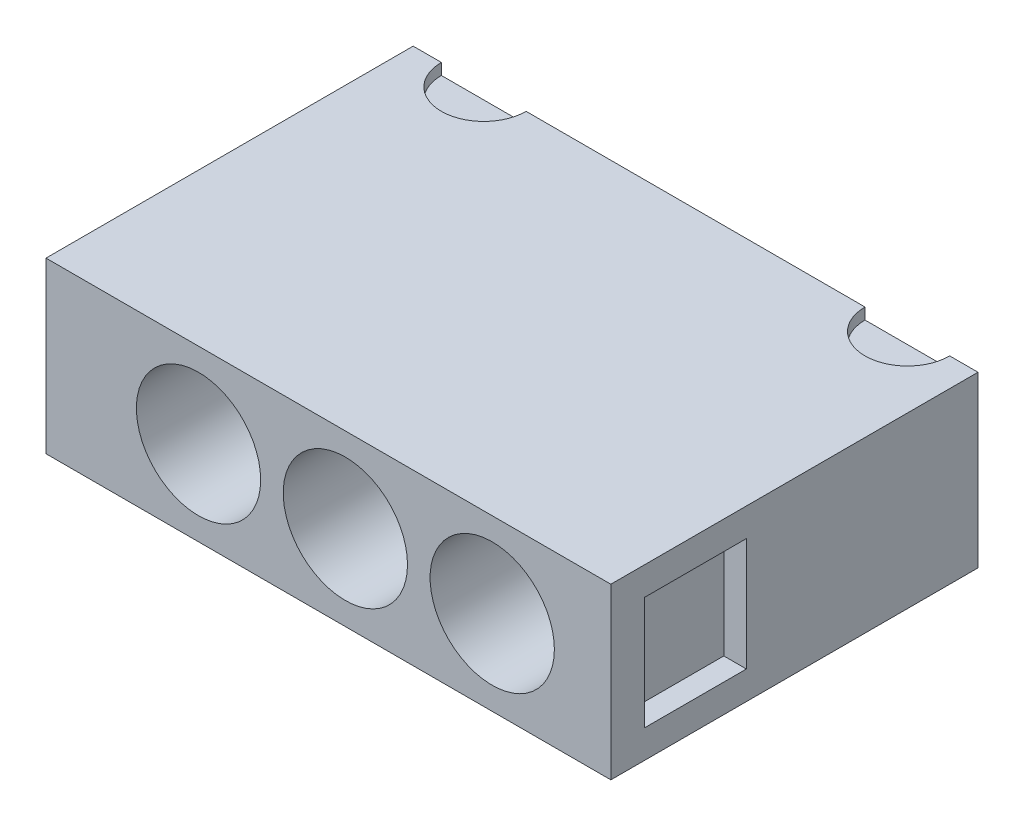
SolidWorks part; units mm, degrees
other "Markup1"
sketch "Sketch6" plane through (0, 0, 650) normal (-1, 0, 0) x (0, 0, -1)
other "DetailItem1"
ref_plane "Front Plane" through (0, 0, 0) normal (0, 0, 1) x (1, 0, 0)
ref_plane "Top Plane" through (0, 0, 0) normal (0, 1, 0) x (1, 0, 0)
ref_plane "Right Plane" through (0, 0, 0) normal (1, 0, 0) x (0, 0, -1)
sketch "Sketch3" plane through (0, 0, 0) normal (0, 0, 1) x (1, 0, 0)
  line L1 (0, 300) -> (1000, 300)
  line L2 (0, 300) -> (0, 0)
  line L3 (0, 0) -> (1000, 0)
  line L4 (1000, 300) -> (1000, 0)
extrude "Boss-Extrude2" add sketch "Sketch3" along normal blind 650
sketch "Sketch4" plane through (1000, 0, 0) normal (1, 0, 0) x (0, 0, -1)
  line L1 (-590, 250) -> (-410, 250)
  line L2 (-590, 250) -> (-590, 50)
  line L3 (-590, 50) -> (-410, 50)
  line L4 (-410, 250) -> (-410, 50)
extrude "Cut-Extrude2" cut sketch "Sketch4" against normal blind 40
sketch "Sketch5" plane through (0, 0, 0) normal (-1, 0, 0) x (0, 0, 1)
  line L0 (650, 300) -> (0, 300) construction
  line L1 (30, 260) -> (230, 260)
  line L2 (30, 260) -> (30, 40)
  line L3 (30, 40) -> (230, 40)
  line L4 (230, 260) -> (230, 40)
  line L5 (650, 0) -> (0, 0) construction
  dimension "D1" = 40
  dimension "D2" = 40
extrude "Cut-Extrude3" cut sketch "Sketch5" against normal blind 650
sketch "Sketch9" plane through (0, 0, 650) normal (0, 0, 1) x (1, 0, 0)
  circle A0 centre (270, 150) radius 110
  circle A1 centre (530, 150) radius 110
  circle A2 centre (790, 150) radius 110
  dimension "D1" = 260
  dimension "D2" = 260
extrude "Cut-Extrude4" cut sketch "Sketch9" against normal blind 500
sketch "Sketch10" plane through (0, 0, 650) normal (0, 0, 1) x (1, 0, 0)
  line L0 (160, 300) -> (160, 0)
  line L1 (0, 0) -> (1000, 0) construction
  dimension "D1" = 300
sketch "Sketch12" plane through (0, 300, 0) normal (0, 1, 0) x (1, 0, 0)
  line L0 (-165, 0) -> (165, 0) construction
  line L1 (50, 0) -> (200, 0)
  line L2 (800, 0) -> (950, 0)
  arc A0 (200, 0) -> (50, 0) centre (125, 0) cw
  arc A1 (800, 0) -> (950, 0) centre (875, 0) ccw
sketch "Sketch16" plane through (0, 300, 0) normal (0, 1, 0) x (1, 0, 0)
  line L0 (50, 0) -> (200, 0)
  line L1 (800, 0) -> (950, 0)
  arc A0 (200, 0) -> (50, 0) centre (125, 0) cw
  arc A1 (50, 0) -> (200, 0) centre (125, 0) ccw construction
  arc A2 (950, 0) -> (800, 0) centre (875, 0) cw
  arc A3 (800, 0) -> (950, 0) centre (875, 0) ccw construction
extrude "Cut-Extrude6" cut sketch "Sketch16" against normal blind 20
sketch "Sketch17" plane through (0, 0, 0) normal (0, -1, 0) x (1, 0, 0)
  line L0 (50, 0) -> (200, 0) construction
  line L1 (800, 0) -> (950, 0) construction
  line L2 (950, 0) -> (800, 0)
  line L3 (200, 0) -> (50, 0)
  arc A0 (200, 0) -> (50, 0) centre (125, 0) ccw
  arc A1 (950, 0) -> (800, 0) centre (875, 0) ccw
extrude "Cut-Extrude7" cut sketch "Sketch17" against normal blind 20
sketch "Sketch18" plane through (0, 0, 650) normal (0, 0, 1) x (1, 0, 0)
  line L0 (160, 150) -> (376.0522, 150)
  line L1 (160, 300) -> (160, 0) construction
  line L2 (376.0522, 150) -> (268.0261, 258.0261)
  line L3 (268.0261, 258.0261) -> (160, 150)
  line L4 (270, 40) -> (160, 150)
  line L5 (270, 40) -> (268.0261, 258.0261)
  line L6 (376.0522, 150) -> (270, 40)
  line L7 (530, 260) -> (530, 150)
  line L8 (530, 150) -> (420, 150)
  line L9 (420, 150) -> (530, 260)
  line L10 (530, 260) -> (640, 150)
  line L11 (640, 150) -> (530, 150)
  line L12 (530, 150) -> (530, 40)
  line L13 (530, 40) -> (640, 150)
  line L14 (530, 40) -> (420, 150)
  circle A0 centre (270, 150) radius 110 construction
  circle A1 centre (530, 150) radius 110 construction
sketch "Sketch19" plane through (0, 300, 0) normal (0, 1, 0) x (1, 0, 0)
  line L0 (0, -413.6386) -> (227.2465, -389.0608)
  line L1 (227.2465, -389.0608) -> (41.9434, -492.8282)
  line L2 (41.9434, -492.8282) -> (113.6232, -401.3497)
  line L3 (113.6232, -401.3497) -> (214.6334, -272.4397)
  line L4 (214.6334, -272.4397) -> (0, -413.6386)
  line L5 (275.3027, -389.0608) -> (275.3027, -492.8282)
  line L6 (275.3027, -492.8282) -> (366.7812, -401.3497)
  line L7 (366.7812, -401.3497) -> (275.3027, -389.0608)
  line L8 (366.7812, -401.3497) -> (458.2597, -413.6386)
  line L9 (458.2597, -413.6386) -> (474.8406, -290.2101)
  line L10 (474.8406, -290.2101) -> (366.7812, -401.3497)
sketch "Sketch20" plane through (0, 0, 230) normal (0, 0, -1) x (-1, 0, 0)
  line L0 (-590, 40) -> (-442.9682, 145.3942)
  line L1 (-650, 40) -> (-530, 40) construction
  line L2 (-442.9682, 145.3942) -> (-625.0778, 73.6242)
  line L3 (-625.0778, 73.6242) -> (-590, 40)
  line L4 (-579.3821, 248.2924) -> (-490.6794, 224.8674)
  line L5 (-490.6794, 224.8674) -> (-636.0217, 120.6843)
  line L6 (-636.0217, 120.6843) -> (-579.3821, 248.2924)
  line L7 (-388.3367, 145.3942) -> (-262.2042, 248.2924)
  line L8 (-262.2042, 248.2924) -> (-388.3367, 109.5092)
  line L9 (-388.3367, 109.5092) -> (-388.3367, 145.3942)
  line L10 (-388.3367, 109.5092) -> (-345.3467, 56.8121)
  line L11 (-345.3467, 56.8121) -> (-211.2686, 222.6383)
  line L12 (-211.2686, 222.6383) -> (-302.3567, 40)
  line L13 (-530, 40) -> (-270, 40) construction
  line L14 (-302.3567, 40) -> (-345.3467, 56.8121)
  arc A0 (-530, 260) -> (-530, 40) centre (-530, 150) ccw construction
  point P13 (0, 0)
  point P20 (-442.9682, 145.3942)
  arc M2 (-270, 40) -> (-270, 260) centre (-270, 150) cw
extrude "Boss-Extrude5" add sketch "Sketch20" against normal blind 36 contours L8 L7 M2 | L12 L11 M2 | L6 L5 L4 | L2 L3 L0
